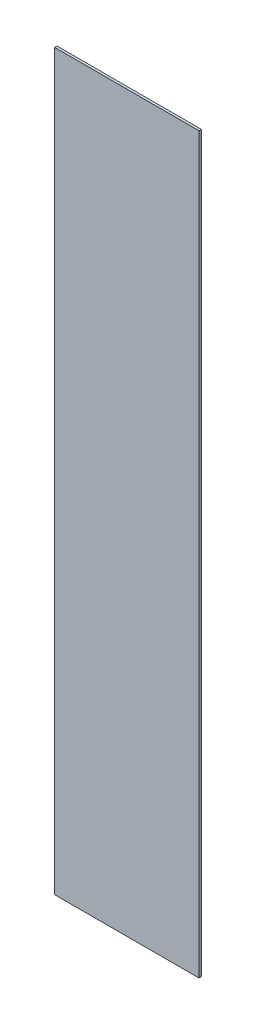
SolidWorks part; units mm, degrees
ref_plane "Front Plane" through (0, 0, 0) normal (0, 0, 1) x (1, 0, 0)
ref_plane "Top Plane" through (0, 0, 0) normal (0, 1, 0) x (1, 0, 0)
ref_plane "Right Plane" through (0, 0, 0) normal (1, 0, 0) x (0, 0, -1)
sketch "Sketch1" plane through (0, 0, 0) normal (0, 0, 1) x (1, 0, 0)
  line L1 (-60, 305) -> (60, 305)
  line L2 (-60, 305) -> (-60, -305)
  line L3 (-60, -305) -> (60, -305)
  line L4 (60, 305) -> (60, -305)
  line L5 (-60, 305) -> (60, -305) construction
  line L6 (-60, -305) -> (60, 305) construction
  point P0 (0, 0)
  dimension "D1" = 610
  dimension "D2" = 120
extrude "Boss-Extrude1" add sketch "Sketch1" along normal blind 2
